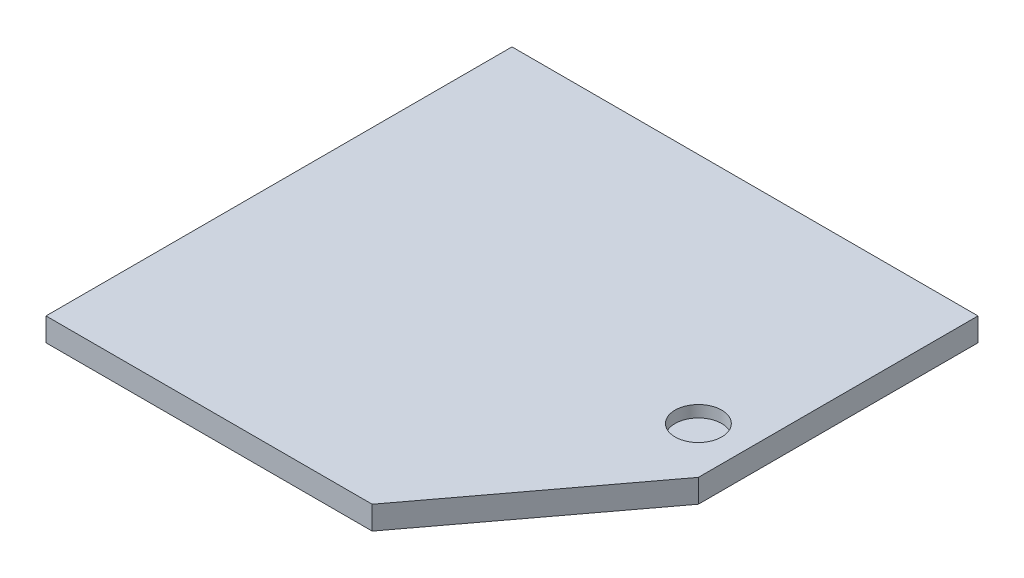
SolidWorks part; units mm, degrees
material "Бук"
ref_plane "Спереди" through (0, 0, 0) normal (0, 0, 1) x (1, 0, 0)
ref_plane "Сверху" through (0, 0, 0) normal (0, 1, 0) x (1, 0, 0)
ref_plane "Справа" through (0, 0, 0) normal (1, 0, 0) x (0, 0, -1)
sketch "Эскиз1" plane through (0, 0, 0) normal (0, 1, 0) x (1, 0, 0)
  line L1 (0, 0) -> (140, 0)
  line L2 (0, 0) -> (0, 200)
  line L3 (0, 200) -> (140, 200)
  line L4 (200, 80) -> (200, 120)
  line L5 (200, 80) -> (140, 0)
  line L6 (140, 200) -> (200, 200)
  line L7 (200, 200) -> (200, 120)
  dimension "D3" = 80
  dimension "D1" = 140
  dimension "D2" = 200
  dimension "D4" = 80
  dimension "D5" = 140
  dimension "D6" = 60
extrude "Бобышка-Вытянуть1" add sketch "Эскиз1" along normal blind 10
sketch "Эскиз2" plane through (0, 10, 0) normal (0, 1, 0) x (1, 0, 0)
  line L0 (0, 100) -> (200, 100) construction
  line L1 (0, 200) -> (0, 0) construction
  line L2 (200, 80) -> (200, 200) construction
  circle A0 centre (180, 100) radius 10
  dimension "D1" = 20
  dimension "D2" = 20
extrude "Вырез-Вытянуть1" cut sketch "Эскиз2" against normal blind 5
